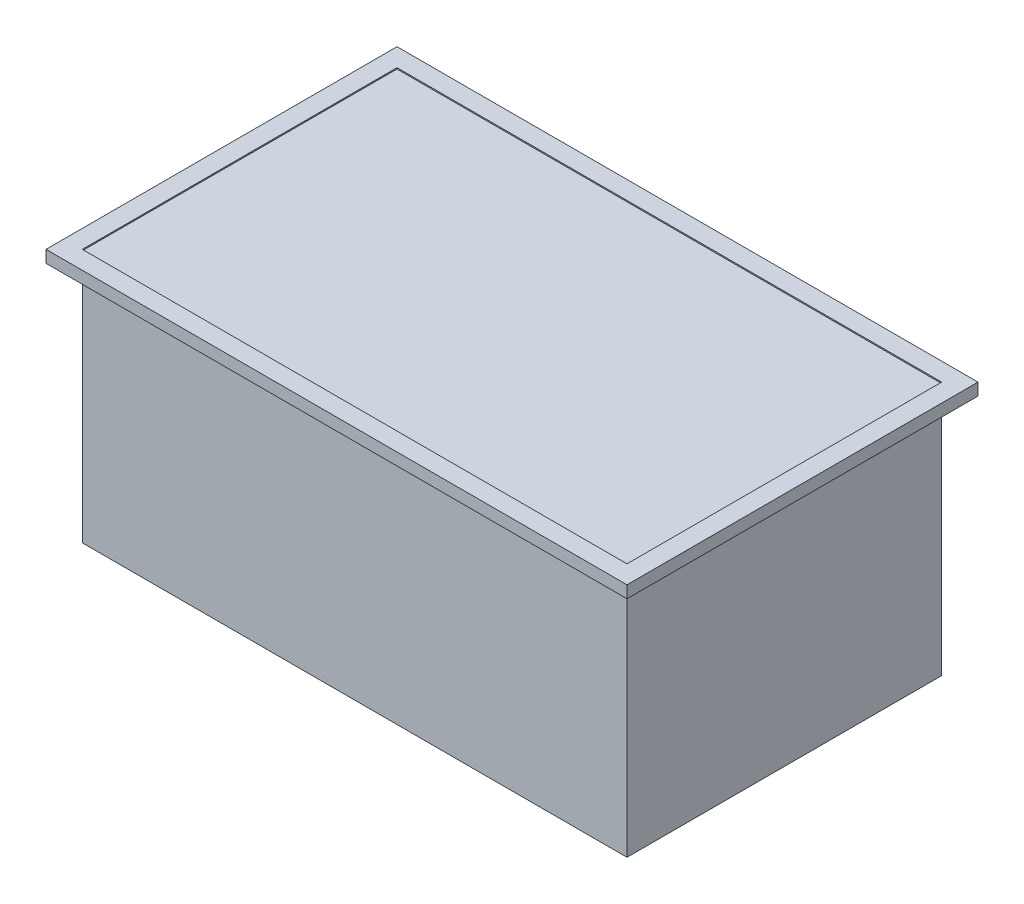
SolidWorks part; units mm, degrees
ref_plane "前视基准面" through (0, 0, 0) normal (0, 0, 1) x (1, 0, 0)
ref_plane "上视基准面" through (0, 0, 0) normal (0, 1, 0) x (1, 0, 0)
ref_plane "右视基准面" through (0, 0, 0) normal (1, 0, 0) x (0, 0, -1)
sketch "草图1" plane through (0, 0, 0) normal (0, 1, 0) x (1, 0, 0)
  line L1 (-22.5, 13) -> (22.5, 13)
  line L2 (-22.5, 13) -> (-22.5, -13)
  line L3 (-22.5, -13) -> (22.5, -13)
  line L4 (22.5, 13) -> (22.5, -13)
  line L5 (-22.5, 13) -> (22.5, -13) construction
  line L6 (-22.5, -13) -> (22.5, 13) construction
  point P0 (0, 0)
  dimension "D1" = 45
  dimension "D2" = 26
extrude "凸台-拉伸4" add sketch "草图1" along normal blind 20
sketch "草图3" plane through (0, 20, 0) normal (0, 1, 0) x (1, 0, 0)
  line L1 (-24, 14.5) -> (24, 14.5)
  line L2 (-24, 14.5) -> (-24, -14.5)
  line L3 (-24, -14.5) -> (24, -14.5)
  line L4 (24, 14.5) -> (24, -14.5)
  line L5 (-24, 14.5) -> (24, -14.5) construction
  line L6 (-24, -14.5) -> (24, 14.5) construction
  point P0 (0, 0)
  dimension "D1" = 48
  dimension "D2" = 29
extrude "凸台-拉伸5" add sketch "草图3" along normal blind 1
sketch "草图4" plane through (0, 21, 0) normal (0, 1, 0) x (1, 0, 0)
  line L1 (-22.5, 13) -> (22.5, 13)
  line L2 (-22.5, 13) -> (-22.5, -13)
  line L3 (-22.5, -13) -> (22.5, -13)
  line L4 (22.5, 13) -> (22.5, -13)
  line L5 (-22.5, 13) -> (22.5, -13) construction
  line L6 (-22.5, -13) -> (22.5, 13) construction
  point P0 (0, 0)
  dimension "D1" = 45
  dimension "D2" = 26
extrude "切除-拉伸1" cut sketch "草图4" against normal blind 0.1
